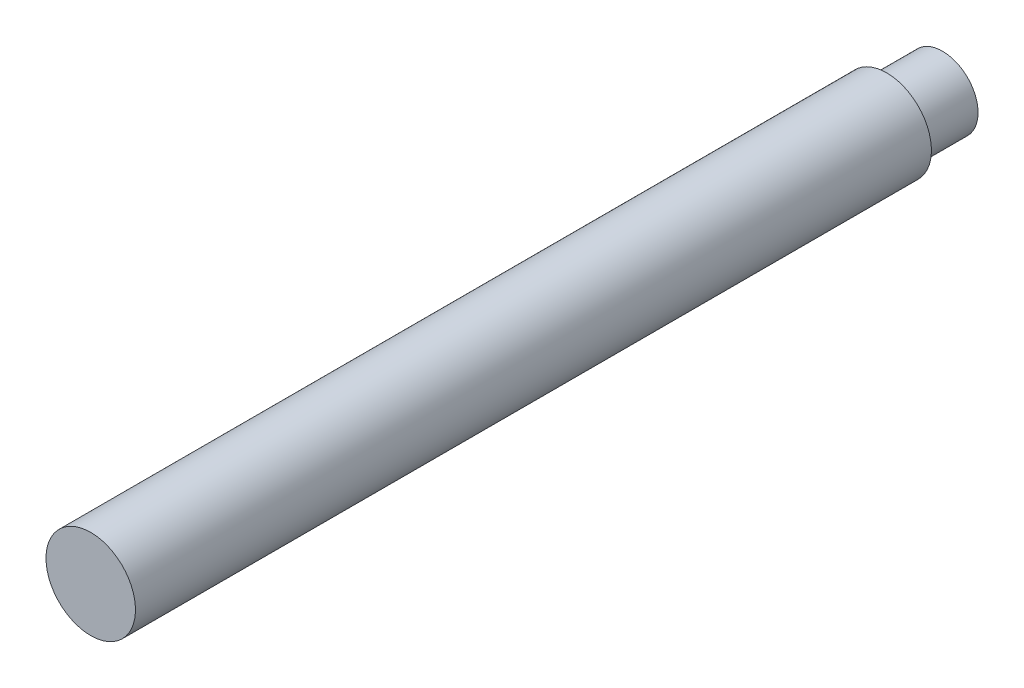
SolidWorks part; units mm, degrees
material "Plain Carbon Steel"
ref_plane "Front Plane" through (0, 0, 0) normal (0, 0, 1) x (1, 0, 0)
ref_plane "Top Plane" through (0, 0, 0) normal (0, 1, 0) x (1, 0, 0)
ref_plane "Right Plane" through (0, 0, 0) normal (1, 0, 0) x (0, 0, -1)
sketch "Sketch1" plane through (0, 0, 0) normal (0, 0, 1) x (1, 0, 0)
  circle A0 centre (0, 0) radius 4.0005
  dimension "D1" = 8.001
extrude "Boss-Extrude1" add sketch "Sketch1" along normal blind 76.2
sketch "Sketch2" plane through (0, 0, 0) normal (0, 0, -1) x (-1, 0, 0)
  circle A0 centre (0, 0) radius 3.175
  circle A1 centre (0, 0) radius 6.4669
  dimension "D1" = 6.35
extrude "Cut-Extrude1" cut sketch "Sketch2" against normal blind 5
